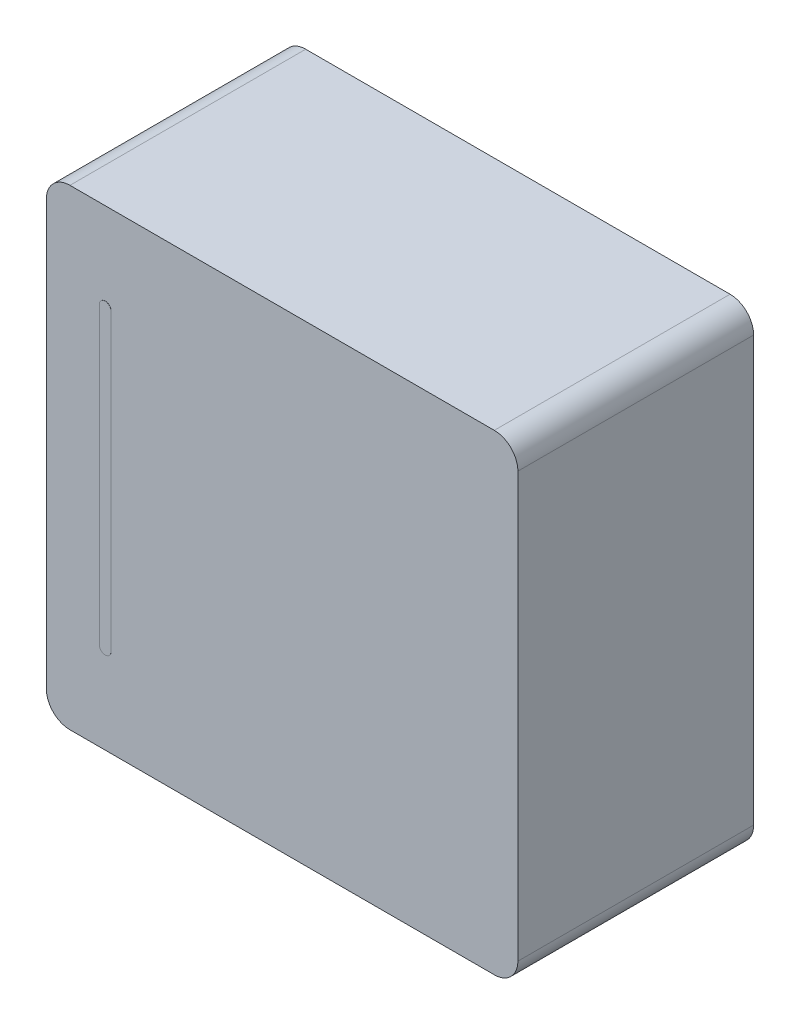
SolidWorks part; units mm, degrees
ref_plane "Plan de face" through (0, 0, 0) normal (0, 0, 1) x (1, 0, 0)
ref_plane "Plan de dessus" through (0, 0, 0) normal (0, 1, 0) x (1, 0, 0)
ref_plane "Plan de droite" through (0, 0, 0) normal (1, 0, 0) x (0, 0, -1)
sketch "Esquisse2" plane through (0, 0, 0) normal (0, 0, 1) x (1, 0, 0)
  line L0 (0, 1.1607) -> (0, -1.1607) construction
  line L1 (-1.675, -1.7) -> (-0.695, -1.7)
  line L2 (-1.675, -1.7) -> (-1.675, 1.7)
  line L3 (-1.675, 1.7) -> (-0.695, 1.7)
  line L4 (-0.695, -1.7) -> (-0.695, 1.7)
  line L5 (-1.675, -1.7) -> (-0.695, 1.7) construction
  line L6 (-1.675, 1.7) -> (-0.695, -1.7) construction
  line L7 (1.675, -1.7) -> (0.695, -1.7)
  line L8 (1.675, -1.7) -> (1.675, 1.7)
  line L9 (1.675, 1.7) -> (0.695, 1.7)
  line L10 (0.695, -1.7) -> (0.695, 1.7)
  line L11 (1.185, 1.7) -> (1.185, -1.7) construction
  point P0 (-1.185, 0)
  dimension "D1" = 0.98
  dimension "D2" = 3.4
  dimension "D3" = 2.37
extrude "pads" add sketch "Esquisse2" along normal blind 0.1
sketch "Esquisse1" plane through (0, 0, 0.1) normal (0, 0, 1) x (1, 0, 0)
  line L1 (-1.8, 2) -> (1.8, 2)
  line L2 (-2, 1.8) -> (-2, -1.8)
  line L3 (-1.8, -2) -> (1.8, -2)
  line L4 (2, 1.8) -> (2, -1.8)
  line L5 (-2, 2) -> (2, -2) construction
  line L6 (-2, -2) -> (2, 2) construction
  arc A0 (2, -1.8) -> (1.8, -2) centre (1.8, -1.8) cw
  arc A1 (-1.8, -2) -> (-2, -1.8) centre (-1.8, -1.8) cw
  arc A2 (-2, 1.8) -> (-1.8, 2) centre (-1.8, 1.8) cw
  arc A3 (1.8, 2) -> (2, 1.8) centre (1.8, 1.8) cw
  point P0 (0, 0)
  dimension "D3" = 0.2
  dimension "D1" = 4
  dimension "D2" = 4
extrude "body" add sketch "Esquisse1" along normal blind 2
sketch "Esquisse3" plane through (0, 0, 2.1) normal (0, 0, 1) x (1, 0, 0)
  line L0 (-1.5, -1.25) -> (-1.5, 1.25) construction
  line L1 (-1.55, -1.25) -> (-1.55, 1.25)
  line L2 (-1.45, -1.25) -> (-1.45, 1.25)
  line L4 (-2, 1.8) -> (-2, -1.8) construction
  arc A0 (-1.55, -1.25) -> (-1.45, -1.25) centre (-1.5, -1.25) ccw
  arc A1 (-1.45, 1.25) -> (-1.55, 1.25) centre (-1.5, 1.25) ccw
  point P2 (-1.5, 0)
  point P7 (0, 0)
  dimension "D1" = 0.1
  dimension "D2" = 2.5
  dimension "D3" = 0.5
extrude "mark" add sketch "Esquisse3" along normal blind 0.001
